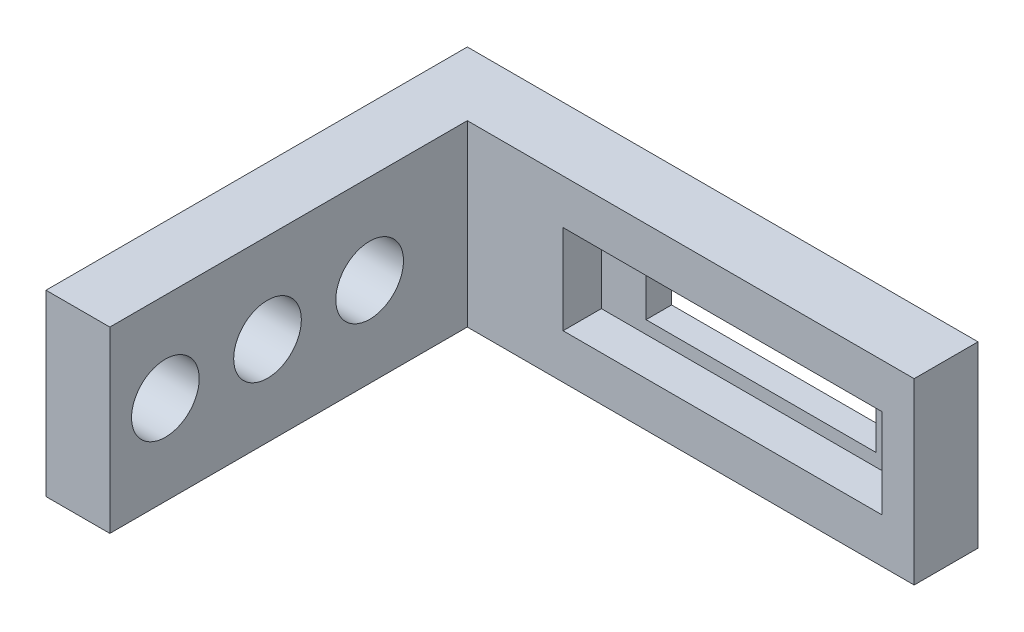
SolidWorks part; units mm, degrees
ref_plane "Front Plane" through (0, 0, 0) normal (0, 0, 1) x (1, 0, 0)
ref_plane "Top Plane" through (0, 0, 0) normal (0, 1, 0) x (1, 0, 0)
ref_plane "Right Plane" through (0, 0, 0) normal (1, 0, 0) x (0, 0, -1)
sketch "Sketch1" plane through (0, 0, 0) normal (0, 1, 0) x (1, 0, 0)
  line L2 (6.5891, 0) -> (10, 0)
  line L8 (0, 9) -> (11.5891, 9)
  line L10 (11.5891, 9) -> (40, 9)
  line L11 (40, 9) -> (40, 4)
  line L13 (6.5891, 0) -> (0, 0)
  line L15 (0, 0) -> (0, 9)
  line L17 (0, 0) -> (37.5449, 0) construction
  line L18 (10, 0) -> (10, 4)
  line L19 (10, 4) -> (40, 4)
  line L20 (25, 4) -> (25, 9) construction
  point P1 (0, 0)
  dimension "D2" = 25
  dimension "D4" = 30
  dimension "D9" = 5
  dimension "D10" = 4
extrude "Boss-Extrude1" add sketch "Sketch1" along normal blind 14
sketch "Sketch2" plane through (0, 0, -4) normal (0, 0, 1) x (1, 0, 0)
  line L0 (40, 7) -> (10, 7) construction
  line L1 (37.5, 3.5) -> (12.5, 3.5)
  line L2 (37.5, 3.5) -> (37.5, 10.5)
  line L3 (37.5, 10.5) -> (12.5, 10.5)
  line L4 (12.5, 3.5) -> (12.5, 10.5)
  line L6 (40, 14) -> (40, 0) construction
  line L7 (25, 3.5) -> (25, 10.5) construction
  line L8 (10, 14) -> (10, 0) construction
  line L11 (37.5, 7) -> (12.5, 7) construction
  line L14 (25, 14) -> (25, 0) construction
  line L15 (10, 14) -> (40, 14) construction
  line L16 (10, 0) -> (40, 0) construction
  dimension "D1" = 25
  dimension "D2" = 7
extrude "Cut-Extrude3" cut sketch "Sketch2" against normal blind 3
sketch "Sketch10" plane through (0, 0, -7) normal (0, 0, 1) x (1, 0, 0)
  line L0 (25, 10.5) -> (25, 3.5) construction
  line L1 (34, 9.5) -> (16, 9.5)
  line L2 (34, 9.5) -> (34, 4.5)
  line L3 (34, 4.5) -> (16, 4.5)
  line L4 (16, 9.5) -> (16, 4.5)
  line L5 (34, 9.5) -> (16, 4.5) construction
  line L6 (34, 4.5) -> (16, 9.5) construction
  line L7 (37.5, 10.5) -> (12.5, 10.5) construction
  line L8 (12.5, 3.5) -> (37.5, 3.5) construction
  line L9 (12.5, 7) -> (37.5, 7) construction
  line L10 (12.5, 10.5) -> (12.5, 3.5) construction
  line L11 (37.5, 3.5) -> (37.5, 10.5) construction
  point P0 (25, 7)
  point P11 (25, 9.5)
  point P18 (16, 7)
  dimension "D1" = 18
  dimension "D2" = 5
extrude "Cut-Extrude4" cut sketch "Sketch10" against normal through all
sketch "Sketch11" plane through (0, 0, 0) normal (-1, 0, 0) x (0, 0, 1)
  line L7 (-9, 14) -> (0, 14) construction
  line L12 (-5, 14) -> (-5, 24)
  line L18 (0, 14) -> (0, 15)
  line L20 (-5, 14) -> (0, 14)
  line L23 (-5, 24) -> (-2.8009, 24)
  line L24 (-2.8009, 24) -> (-2.8009, 15)
  line L25 (-2.8009, 15) -> (0, 15)
  dimension "D1" = 9
  dimension "D2" = 5
  dimension "D3" = 10
extrude "Boss-Extrude8" [suppressed] add sketch "Sketch11" against normal blind 3
sketch "Sketch12" [suppressed] plane through (3, 0, 0) normal (1, 0, 0) x (0, 0, -1)
  line L0 (2.8009, 15) -> (2.8009, 24) construction
  line L1 (8.4206, 15) -> (2.8009, 15) construction
  circle A0 centre (5.3009, 17.5) radius 2.5
  dimension "D1" = 5
extrude "Boss-Extrude9" [suppressed] add sketch "Sketch12" along normal blind 9
ref_plane "Plane1" through (10, 0, 0) normal (-1, 0, 0) x (0, 0, 1)
sketch "Sketch14" [suppressed] plane through (0, 0, -17.4206) normal (0, 0, -1) x (-1, 0, 0)
  line L0 (-59, 0) -> (0, 0) construction
  line L1 (-10, 0) -> (-3, 0)
  line L2 (-10, 0) -> (-10, 12)
  line L3 (-10, 12) -> (-3, 12)
  line L4 (-3, 0) -> (-3, 12)
  line L5 (-3, 24) -> (-3, 14) construction
  dimension "D1" = 12
  dimension "D2" = 7
sketch "Sketch15" [suppressed] plane through (0, 0, 0) normal (-1, 0, 0) x (0, 0, 1)
  line L1 (-8.1108, 24) -> (-8.1108, 15.2416) construction
  line L2 (-2.8009, 24) -> (-13.4206, 24) construction
  line L3 (-2.8009, 19.5) -> (-12.1862, 19.5) construction
  line L4 (-2.8009, 15) -> (-2.8009, 24) construction
  circle A0 centre (-8.1108, 19.5) radius 2.5
  dimension "D1" = 5
extrude "Cut-Extrude8" [suppressed] cut sketch "Sketch15" against normal through all
sketch "Sketch16" [suppressed] plane through (0, 0, -17.4206) normal (0, 0, -1) x (-1, 0, 0)
  line L0 (-59, 0) -> (0, 0) construction
  line L1 (-15, 11) -> (-3, 11)
  line L2 (-15, 11) -> (-15, 0)
  line L3 (-15, 0) -> (-3, 0)
  line L4 (-3, 11) -> (-3, 0)
  line L5 (-3, 24) -> (-3, 14) construction
  dimension "D1" = 12
  dimension "D2" = 11
extrude "Cut-Extrude9" [suppressed] cut sketch "Sketch16" against normal blind 9
sketch "Sketch19" [suppressed] plane through (0, 0, -17.4206) normal (0, 0, -1) x (-1, 0, 0)
  line L0 (-59, 0) -> (0, 0) construction
  line L1 (-13.7627, 0) -> (-3, 0)
  line L2 (-13.7627, 0) -> (-13.7627, 11.672)
  line L3 (-13.7627, 11.672) -> (-3, 11.672)
  line L4 (-3, 0) -> (-3, 11.672)
  line L5 (-3, 24) -> (-3, 14) construction
extrude "Cut-Extrude12" [suppressed] cut sketch "Sketch19" against normal blind 7
sketch "Sketch20" plane through (0, 0, 0) normal (-1, 0, 0) x (0, 0, 1)
  line L0 (-4, 14) -> (-4, 0) construction
  line L1 (0, 0) -> (24, 0)
  line L2 (0, 0) -> (0, 14)
  line L3 (0, 14) -> (24, 14)
  line L4 (24, 0) -> (24, 14)
  point P5 (0, 0)
  dimension "D1" = 28
extrude "Boss-Extrude10" add sketch "Sketch20" against normal blind 5
sketch "Sketch21" plane through (0, 0, 0) normal (-1, 0, 0) x (0, 0, 1)
  line L0 (-9, 14) -> (-9, 0) construction
  line L1 (-9, 7) -> (24, 7) construction
  line L2 (24, 0) -> (24, 14) construction
  circle A0 centre (-4.35, 7) radius 2.65
  circle A3 centre (3.65, 7) radius 2.65
  circle A4 centre (11.65, 7) radius 2.65
  circle A5 centre (19.65, 7) radius 2.65
  dimension "D1" = 5.3
  dimension "D2" = 4.65
  dimension "D3" = 4
extrude "Cut-Extrude13" cut sketch "Sketch21" against normal up to surface (5 mm away) contours A0 | A3 | A4 | A5 up to face at (5, 7, 12)
sketch "Sketch22" plane through (0, 14, 0) normal (0, 1, 0) x (1, 0, 0)
  line L0 (10, 7.7) -> (10, -7.7) construction
  line L1 (5, 0) -> (10, 0)
  line L2 (5, 0) -> (5, 4)
  line L3 (5, 4) -> (10, 4)
  line L4 (10, 0) -> (10, 4)
  line L5 (10, 4) -> (40, 4) construction
  point P7 (0, 0)
extrude "Cut-Extrude14" cut sketch "Sketch22" against normal through all
sketch "Sketch23" plane through (0, 0, 0) normal (-1, 0, 0) x (0, 0, 1)
  circle A0 centre (-4.35, 7) radius 2.65
extrude "Boss-Extrude11" add sketch "Sketch23" against normal up to surface (5 mm away) up to face at (5, 7, 1)
